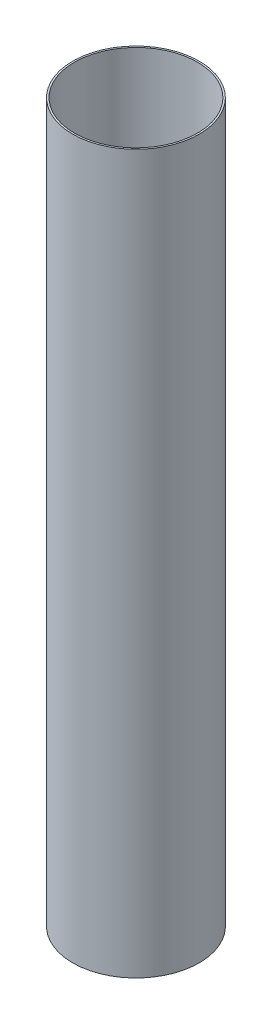
SolidWorks part; units mm, degrees
ref_plane "Front Plane" through (0, 0, 0) normal (0, 0, 1) x (1, 0, 0)
ref_plane "Top Plane" through (0, 0, 0) normal (0, 1, 0) x (1, 0, 0)
ref_plane "Right Plane" through (0, 0, 0) normal (1, 0, 0) x (0, 0, -1)
sketch "Sketch1" plane through (0, 0, 0) normal (0, 1, 0) x (1, 0, 0)
  circle A0 centre (0, 0) radius 76.2
  circle A1 centre (0, 0) radius 78.359
  dimension "D1" = 156.718
  dimension "D2" = 152.4
extrude "Boss-Extrude1" add sketch "Sketch1" along normal blind 889
equation "\"Length\"= 35in"
equation "\"D1@Boss-Extrude1\"=\"Length\""
